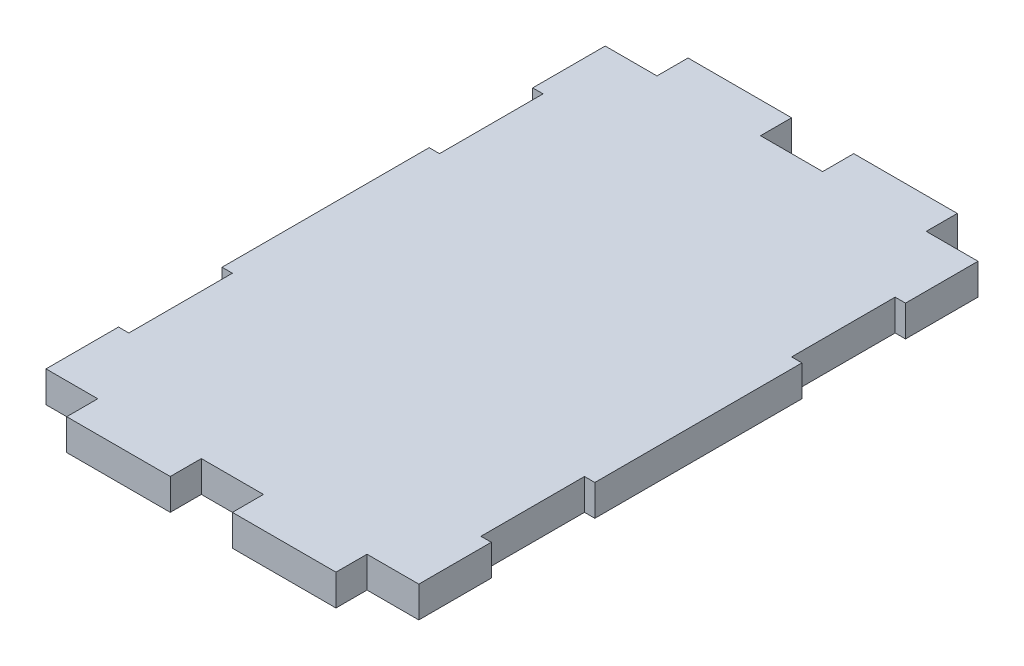
SolidWorks part; units mm, degrees
material "Acrylic (Medium-high impact)"
ref_plane "Front Plane" through (0, 0, 0) normal (0, 0, 1) x (1, 0, 0)
ref_plane "Top Plane" through (0, 0, 0) normal (0, 1, 0) x (1, 0, 0)
ref_plane "Right Plane" through (0, 0, 0) normal (1, 0, 0) x (0, 0, -1)
sketch "Sketch1" plane through (0, 0, 0) normal (0, 1, 0) x (1, 0, 0)
  line L0 (1, 30) -> (35, 30) construction
  line L1 (0, 0) -> (36, 0) construction
  line L2 (0, 0) -> (0, 60) construction
  line L3 (0, 60) -> (36, 60) construction
  line L4 (36, 0) -> (36, 60) construction
  line L5 (1, 3) -> (35, 3)
  line L6 (1, 3) -> (1, 57)
  line L7 (1, 57) -> (35, 57)
  line L8 (35, 3) -> (35, 57)
  line L10 (5, 3) -> (5, 0)
  line L11 (5, 0) -> (15, 0)
  line L12 (15, 3) -> (15, 0)
  line L14 (21, 3) -> (21, 0)
  line L15 (21, 0) -> (31, 0)
  line L16 (31, 3) -> (31, 0)
  line L17 (18, 3) -> (18, 57) construction
  line L18 (0, 3) -> (1, 3)
  line L19 (0, 3) -> (0, 10)
  line L20 (0, 10) -> (1, 10)
  line L22 (0, 50) -> (1, 50)
  line L23 (0, 50) -> (0, 57)
  line L24 (0, 57) -> (1, 57)
  line L26 (21, 60) -> (31, 60)
  line L27 (0, 40) -> (1, 40)
  line L28 (0, 40) -> (0, 20)
  line L29 (0, 20) -> (1, 20)
  line L31 (31, 57) -> (31, 60)
  line L33 (21, 57) -> (21, 60)
  line L34 (5, 60) -> (15, 60)
  line L35 (15, 57) -> (15, 60)
  line L37 (5, 57) -> (5, 60)
  line L38 (36, 10) -> (35, 10)
  line L40 (36, 3) -> (35, 3)
  line L41 (36, 3) -> (36, 10)
  line L42 (36, 57) -> (35, 57)
  line L44 (36, 50) -> (35, 50)
  line L45 (36, 50) -> (36, 57)
  line L46 (36, 20) -> (35, 20)
  line L48 (36, 40) -> (35, 40)
  line L49 (36, 40) -> (36, 20)
  point P9 (18, 3)
  point P10 (18, 0)
  point P11 (0, 30)
  point P12 (1, 30)
  dimension "D1" = 60
  dimension "D2" = 36
  dimension "D3" = 1
  dimension "D4" = 3
  dimension "D5" = 5
  dimension "D6" = 5
  dimension "D7" = 10
  dimension "D8" = 7
  dimension "D9" = 20
  dimension "D10" = 10
extrude "Boss-Extrude1" add sketch "Sketch1" along normal blind 3 contours L5 L8 L7 L6 | L12 L5 L10 L11 | L16 L5 L14 L15 | L40 L41 L38 L8 | L49 L48 L8 L46 | L44 L45 L42 L8 | L33 L7 L31 L26 | L37 L7 L35 L34 | L24 L23 L22 L6 | L28 L29 L6 L27 | L20 L19 L18 L6
